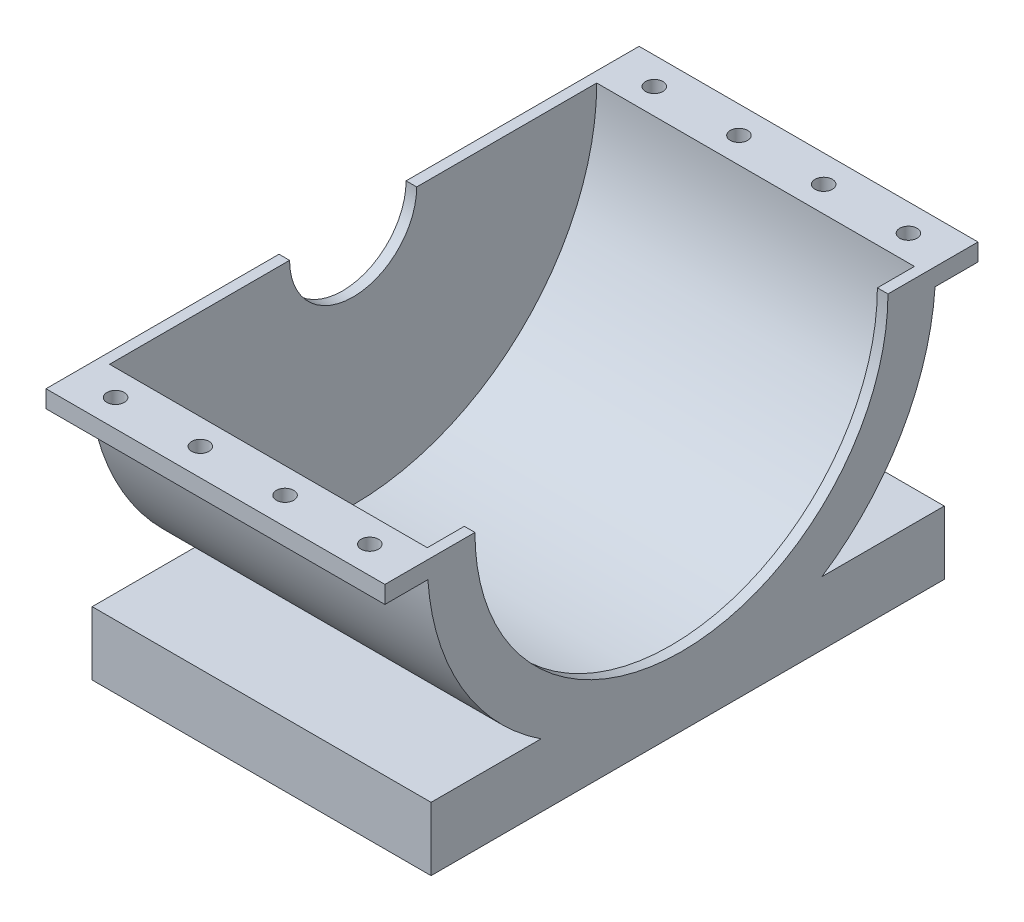
SolidWorks part; units mm, degrees
ref_plane "Front Plane" through (0, 0, 0) normal (0, 0, 1) x (1, 0, 0)
ref_plane "Top Plane" through (0, 0, 0) normal (0, 1, 0) x (1, 0, 0)
ref_plane "Right Plane" through (0, 0, 0) normal (1, 0, 0) x (0, 0, -1)
sketch "Sketch1" plane through (0, 0, 0) normal (1, 0, 0) x (0, 0, -1)
  line L0 (-7, 0) -> (7, 0)
  line L1 (-7, 0) -> (-7, -0.41)
  line L2 (-5.9102, -5) -> (-3.3166, -5)
  line L3 (-5.9102, -5) -> (-5.9102, -6.5)
  line L4 (-5.9102, -6.5) -> (6.2036, -6.5)
  line L5 (6.2036, -5) -> (6.2036, -6.5)
  line L6 (-7, -0.41) -> (-5.986, -0.41)
  line L7 (7, -0.41) -> (7, 0)
  line L8 (5.986, -0.41) -> (7, -0.41)
  line L9 (3.3166, -5) -> (6.2036, -5)
  arc A0 (-5.986, -0.41) -> (-3.3166, -5) centre (0, 0) ccw
  arc A1 (3.3166, -5) -> (5.986, -0.41) centre (0, 0) ccw
  point P5 (0, 0)
  point P6 (0, 0)
  point P12 (-16.1899, 2.7773)
  point P15 (0, 0)
  dimension "D3" = 6
  dimension "D1" = 14
  dimension "D2" = 1.5
  dimension "D4" = 6.5
  dimension "D5" = 5
  dimension "D6" = 7
  dimension "D7" = 0.41
extrude "Boss-Extrude1" add sketch "Sketch1" along normal mid plane 8 contours L6 A0 L2 L8 L7 L0 L1
sketch "Sketch2" plane through (0, 0, 0) normal (1, 0, 0) x (0, 0, -1)
  line L0 (-5.75, 0) -> (5.75, 0)
  arc A0 (-5.75, 0) -> (5.75, 0) centre (0, 0) ccw
  dimension "D1" = 5.75
  dimension "D2" = 5.75
extrude "Cut-Extrude1" cut sketch "Sketch2" against normal mid plane 7.5
sketch "Sketch3" plane through (4, 0, 0) normal (1, 0, 0) x (0, 0, -1)
  line L0 (-7, 0) -> (7, 0) construction
  line L1 (-4.875, 0) -> (4.875, 0)
  arc A0 (-4.875, 0) -> (4.875, 0) centre (0, 0) ccw
  dimension "D1" = 4.875
extrude "Cut-Extrude2" cut sketch "Sketch3" against normal up to next
sketch "Sketch4" plane through (-3.75, 0, 0) normal (1, 0, 0) x (0, 0, -1)
  line L0 (-1.5, 0) -> (1.5, 0)
  arc A0 (-1.5, 0) -> (1.5, 0) centre (0, 0) ccw
  dimension "D1" = 1.5
extrude "Cut-Extrude3" cut sketch "Sketch4" against normal up to next
sketch "Sketch6" plane through (0, 0, 0) normal (0, 1, 0) x (1, 0, 0)
  line L1 (4, 4.875) -> (4, 7) construction
  line L2 (-4, 1.5) -> (-4, 7) construction
  circle A1 centre (3, 6.3574) radius 0.205
  circle A2 centre (1, 6.3574) radius 0.205
  circle A3 centre (-1, 6.3574) radius 0.205
  circle A4 centre (-3, 6.3574) radius 0.205
  point P12 (0, 0)
  point P13 (0, 0)
  point P14 (-4, 6.8744)
  dimension "D3" = 1
  dimension "D2" = 0.41
  dimension "D1" = 4
  dimension "D4" = 2
  dimension "D5" = 1
  dimension "D6" = 2
  dimension "D7" = 2
extrude "Cut-Extrude4" cut sketch "Sketch6" against normal up to next
mirror "Mirror1" about plane through (0, 0, 0) normal (0, 0, 1) of "Cut-Extrude4"
